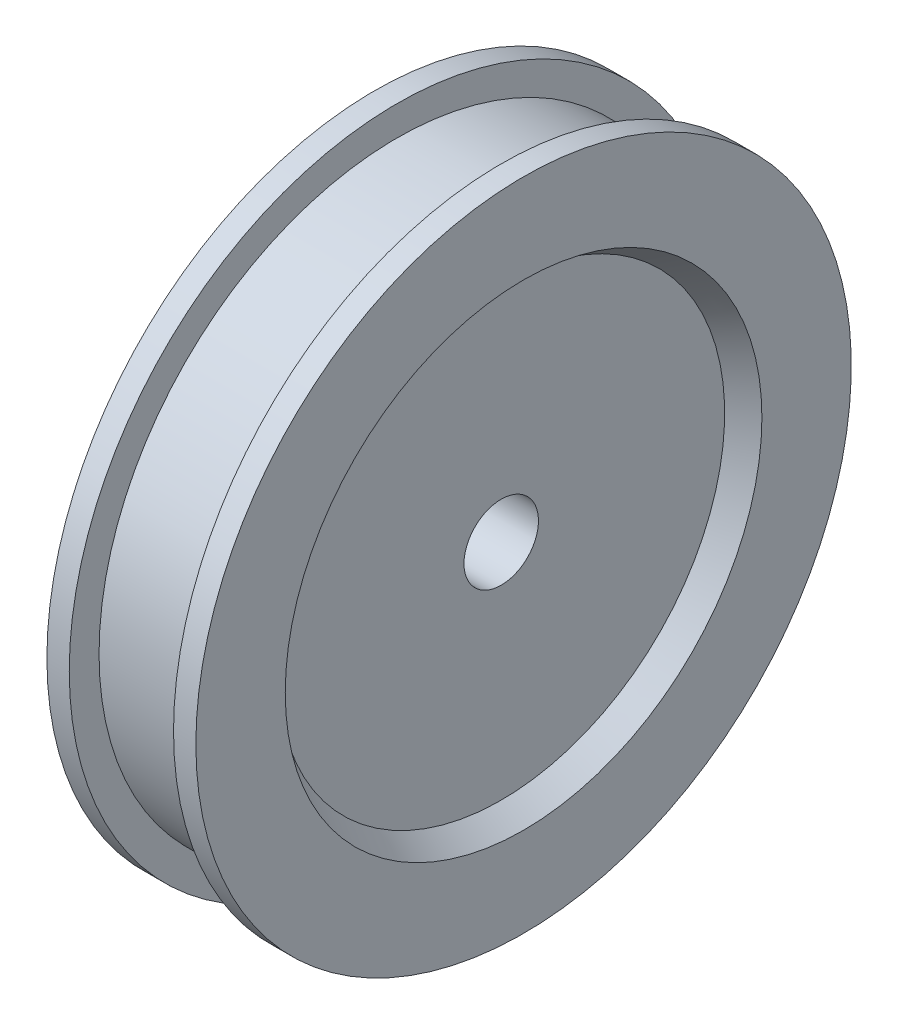
SolidWorks part; units mm, degrees
ref_plane "Front Plane" through (0, 0, 0) normal (0, 0, 1) x (1, 0, 0)
ref_plane "Top Plane" through (0, 0, 0) normal (0, 1, 0) x (1, 0, 0)
ref_plane "Right Plane" through (0, 0, 0) normal (1, 0, 0) x (0, 0, -1)
sketch "Sketch1" plane through (0, 0, 0) normal (0, 0, 1) x (1, 0, 0)
  line L0 (0, 0) -> (0, 44.169) construction
  line L1 (-7, 40) -> (7, 40)
  line L2 (7, 40) -> (7, 44)
  line L3 (7, 44) -> (10, 44)
  line L4 (10, 44) -> (10, 32)
  line L5 (10, 32) -> (7, 30)
  line L6 (7, 30) -> (7, 5)
  line L7 (7, 5) -> (-7, 5)
  line L8 (-7, 30) -> (-7, 5)
  line L9 (-10, 32) -> (-7, 30)
  line L10 (-7, 44) -> (-10, 44)
  line L11 (-7, 40) -> (-7, 44)
  line L12 (-10, 44) -> (-10, 32)
  line L13 (0, 0) -> (4.8392, 0) construction
  point P12 (0, 5)
  point P17 (0, 40)
  dimension "D1" = 5
  dimension "D2" = 2
  dimension "D3" = 25
  dimension "D4" = 12
  dimension "D5" = 7
  dimension "D6" = 3
  dimension "D7" = 40
revolve "Revolve1" add sketch "Sketch1" angle 360 about L13
